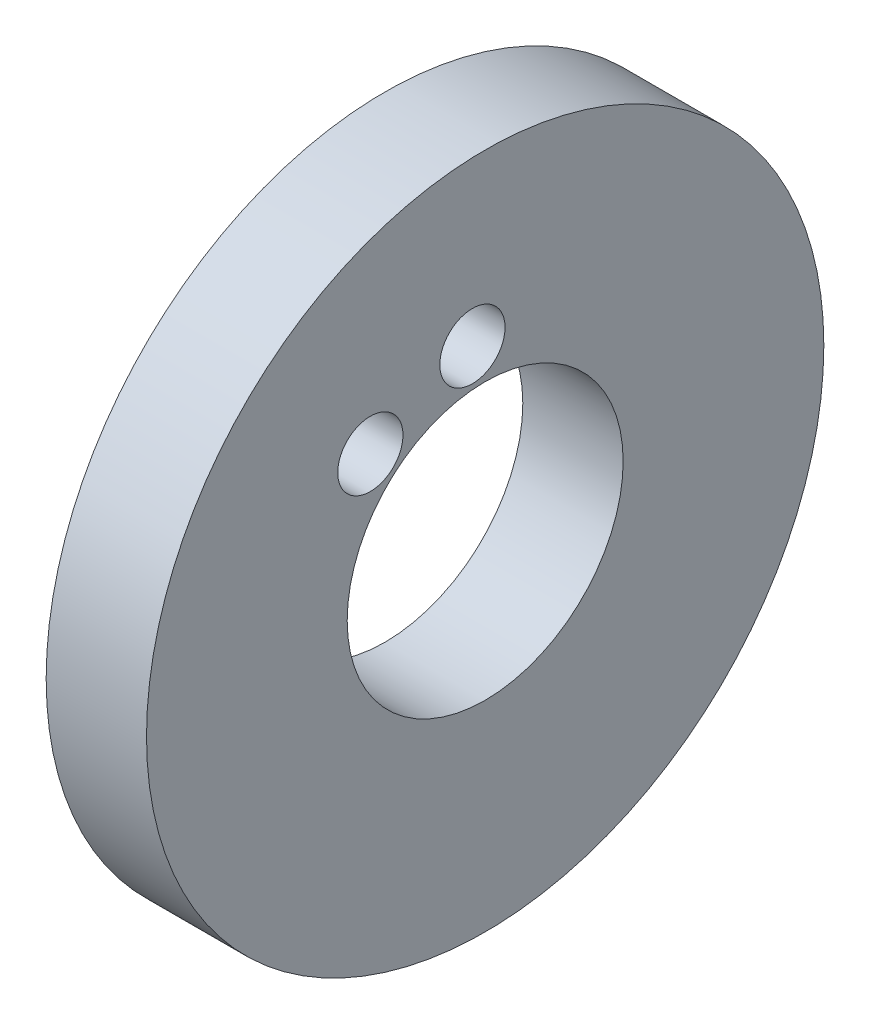
SolidWorks part; units mm, degrees
ref_plane "Front Plane" through (0, 0, 0) normal (0, 0, 1) x (1, 0, 0)
ref_plane "Top Plane" through (0, 0, 0) normal (0, 1, 0) x (1, 0, 0)
ref_plane "Right Plane" through (0, 0, 0) normal (1, 0, 0) x (0, 0, -1)
sketch "Axial profile (mm)" plane through (0, 0, 0) normal (0, 0, 1) x (1, 0, 0)
  line L0 (-110, 0) -> (75, 0) construction
  line L1 (135.7, 11) -> (143.7, 11)
  line L2 (143.7, 11) -> (143.7, 27)
  line L3 (143.7, 27) -> (135.7, 27)
  line L4 (135.7, 27) -> (135.7, 11)
revolve "Full revolution" add sketch "Axial profile (mm)" angle 360 about L0
sketch "Sketch2" plane through (0, 0, 0) normal (1, 0, 0) x (0, 0, -1)
  circle A0 centre (-1.0169, 13.963) radius 2.6
  circle A1 centre (-9.1543, 10.5924) radius 2.6
extrude "Axial holes" cut sketch "Sketch2" against normal through all and the other way through all
